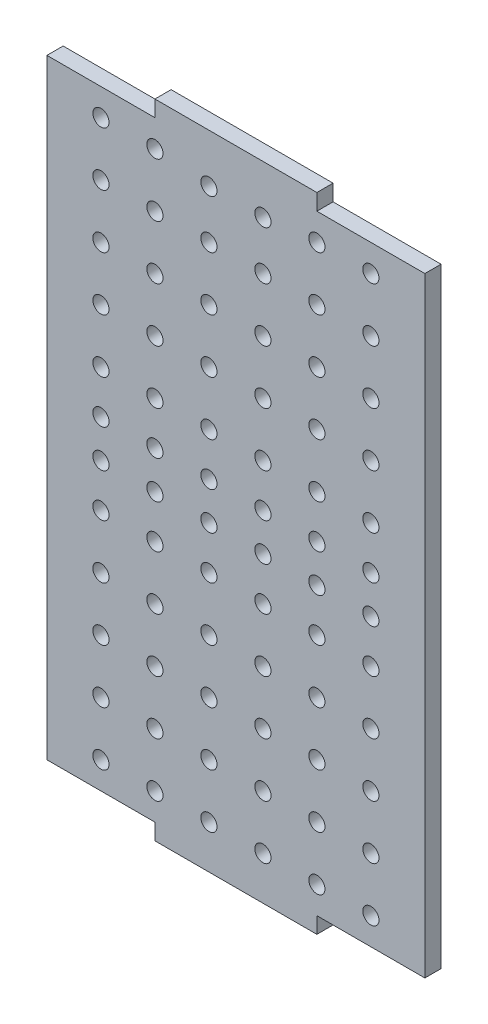
SolidWorks part; units mm, degrees
material "Maple"
ref_plane "Front Plane" through (0, 0, 0) normal (0, 0, 1) x (1, 0, 0)
ref_plane "Top Plane" through (0, 0, 0) normal (0, 1, 0) x (1, 0, 0)
ref_plane "Right Plane" through (0, 0, 0) normal (1, 0, 0) x (0, 0, -1)
sketch "Sketch1" plane through (0, 0, 0) normal (0, 0, 1) x (1, 0, 0)
  line L0 (-25, 56.5) -> (-25, 51.5) construction
  line L2 (-35, 56.5) -> (-35, -56.5)
  line L4 (35, 56.5) -> (35, -56.5)
  line L5 (-35, 56.5) -> (35, -56.5) construction
  line L6 (-35, -56.5) -> (35, 56.5) construction
  line L7 (-35, -56.5) -> (-15, -56.5)
  line L8 (-25, 51.5) -> (-25, 41.5) construction
  line L9 (-25, 41.5) -> (-25, 31.5) construction
  line L10 (-25, 31.5) -> (-25, 21.5) construction
  line L11 (-25, 21.5) -> (-25, 11.5) construction
  line L12 (-25, 11.5) -> (-25, 3.5) construction
  line L13 (-25, 3.5) -> (-25, -3.5) construction
  line L14 (-25, -3.5) -> (-25, -11.5) construction
  line L15 (-25, -11.5) -> (-25, -21.5) construction
  line L16 (-25, -21.5) -> (-25, -31.5) construction
  line L17 (-15, -41.5) -> (-15, -51.5) construction
  line L19 (-25, 41.5) -> (-15, 41.5) construction
  line L20 (25, 51.5) -> (25, 41.5) construction
  line L21 (-15, -56.5) -> (-15, -59.5)
  line L22 (35, -56.5) -> (15, -56.5)
  line L23 (-15, 41.5) -> (-5, 41.5) construction
  line L24 (-15, 51.5) -> (-15, 41.5) construction
  line L25 (-15, 41.5) -> (-15, 31.5) construction
  line L26 (-15, 31.5) -> (-15, 21.5) construction
  line L27 (-15, 21.5) -> (-15, 11.5) construction
  line L28 (-15, 11.5) -> (-15, 3.5) construction
  line L29 (-15, 3.5) -> (-15, -3.5) construction
  line L30 (-15, -3.5) -> (-15, -11.5) construction
  line L31 (-15, -11.5) -> (-15, -21.5) construction
  line L32 (-15, -21.5) -> (-15, -31.5) construction
  line L33 (-25, -41.5) -> (-25, -51.5) construction
  line L34 (25, 41.5) -> (25, 31.5) construction
  line L35 (25, 31.5) -> (25, 21.5) construction
  line L36 (25, 21.5) -> (25, 11.5) construction
  line L37 (-15, 51.5) -> (-15, 56.5) construction
  line L38 (-5, 50.5) -> (-5, 59.5) construction
  line L39 (5, 50.5) -> (5, 59.5) construction
  line L40 (-5, 51.5) -> (-5, 41.5) construction
  line L41 (-5, 41.5) -> (-5, 31.5) construction
  line L42 (-5, 31.5) -> (-5, 21.5) construction
  line L43 (-5, 21.5) -> (-5, 11.5) construction
  line L44 (-5, 11.5) -> (-5, 3.5) construction
  line L45 (-5, 3.5) -> (-5, -3.5) construction
  line L46 (-5, -3.5) -> (-5, -11.5) construction
  line L47 (-5, -11.5) -> (-5, -21.5) construction
  line L48 (-5, -21.5) -> (-5, -31.5) construction
  line L49 (-5, -41.5) -> (-5, -51.5) construction
  line L50 (25, 11.5) -> (25, 3.5) construction
  line L51 (25, 3.5) -> (25, -3.5) construction
  line L52 (25, -3.5) -> (25, -11.5) construction
  line L53 (15, 56.5) -> (15, 51.5) construction
  line L54 (-15, -59.5) -> (15, -59.5)
  line L55 (15, -59.5) -> (15, -56.5)
  line L56 (5, 51.5) -> (5, 41.5) construction
  line L57 (5, 41.5) -> (5, 31.5) construction
  line L58 (5, 31.5) -> (5, 21.5) construction
  line L59 (5, 21.5) -> (5, 11.5) construction
  line L60 (5, 11.5) -> (5, 3.5) construction
  line L61 (5, 3.5) -> (5, -3.5) construction
  line L62 (5, -3.5) -> (5, -11.5) construction
  line L63 (5, -11.5) -> (5, -21.5) construction
  line L64 (5, -21.5) -> (5, -31.5) construction
  line L65 (5, -41.5) -> (5, -51.5) construction
  line L66 (25, -11.5) -> (25, -21.5) construction
  line L67 (25, -21.5) -> (25, -31.5) construction
  line L68 (15, -41.5) -> (15, -51.5) construction
  line L69 (-5, 41.5) -> (5, 41.5) construction
  line L70 (5, 41.5) -> (15, 41.5) construction
  line L71 (15, 41.5) -> (25, 41.5) construction
  line L72 (15, 51.5) -> (15, 41.5) construction
  line L73 (15, 41.5) -> (15, 31.5) construction
  line L74 (15, 31.5) -> (15, 21.5) construction
  line L75 (15, 21.5) -> (15, 11.5) construction
  line L76 (15, 11.5) -> (15, 3.5) construction
  line L77 (15, 3.5) -> (15, -3.5) construction
  line L78 (15, -3.5) -> (15, -11.5) construction
  line L79 (15, -11.5) -> (15, -21.5) construction
  line L80 (15, -21.5) -> (15, -31.5) construction
  line L81 (25, -41.5) -> (25, -51.5) construction
  line L82 (25, 51.5) -> (25, 56.5) construction
  line L83 (-25, 56.5) -> (-15, 56.5)
  line L85 (25, 56.5) -> (35, 56.5)
  line L90 (-15, 56.5) -> (-15, 59.5)
  line L95 (-25, 56.5) -> (-35, 56.5)
  line L98 (25, 56.5) -> (15, 56.5)
  line L99 (15, 56.5) -> (15, 59.5)
  line L100 (15, 59.5) -> (5, 59.5)
  line L103 (-25, -31.5) -> (-25, -41.5) construction
  line L104 (-15, -31.5) -> (-15, -41.5) construction
  line L105 (-5, -31.5) -> (-5, -41.5) construction
  line L106 (5, -31.5) -> (5, -41.5) construction
  line L107 (25, -31.5) -> (25, -41.5) construction
  line L108 (15, -31.5) -> (15, -41.5) construction
  line L112 (-15, 59.5) -> (-5, 59.5)
  line L114 (-5, 59.5) -> (5, 59.5)
  circle A4 centre (-25, 51.5) radius 1.5
  circle A7 centre (-25, 41.5) radius 1.5
  circle A8 centre (-25, 31.5) radius 1.5
  circle A9 centre (-25, 21.5) radius 1.5
  circle A10 centre (-25, 11.5) radius 1.5
  circle A11 centre (-25, 3.5) radius 1.5
  circle A12 centre (-25, -3.5) radius 1.5
  circle A13 centre (-25, -11.5) radius 1.5
  circle A14 centre (-25, -21.5) radius 1.5
  circle A15 centre (-25, -31.5) radius 1.5
  circle A16 centre (-25, -51.5) radius 1.5
  circle A20 centre (-15, 51.5) radius 1.5
  circle A21 centre (-15, 41.5) radius 1.5
  circle A22 centre (-15, 31.5) radius 1.5
  circle A23 centre (-15, 21.5) radius 1.5
  circle A24 centre (-15, 11.5) radius 1.5
  circle A25 centre (-15, 3.5) radius 1.5
  circle A26 centre (-15, -3.5) radius 1.5
  circle A27 centre (-15, -11.5) radius 1.5
  circle A28 centre (-15, -21.5) radius 1.5
  circle A29 centre (-15, -31.5) radius 1.5
  circle A30 centre (-15, -51.5) radius 1.5
  circle A31 centre (-5, 50.5) radius 1.5
  circle A32 centre (-5, 41.5) radius 1.5
  circle A33 centre (-5, 31.5) radius 1.5
  circle A34 centre (-5, 21.5) radius 1.5
  circle A35 centre (-5, 11.5) radius 1.5
  circle A36 centre (-5, 3.5) radius 1.5
  circle A37 centre (-5, -3.5) radius 1.5
  circle A38 centre (-5, -11.5) radius 1.5
  circle A39 centre (-5, -21.5) radius 1.5
  circle A40 centre (-5, -31.5) radius 1.5
  circle A41 centre (-5, -51.5) radius 1.5
  circle A42 centre (5, 50.5) radius 1.5
  circle A43 centre (5, 41.5) radius 1.5
  circle A44 centre (5, 31.5) radius 1.5
  circle A45 centre (5, 21.5) radius 1.5
  circle A46 centre (5, 11.5) radius 1.5
  circle A47 centre (5, 3.5) radius 1.5
  circle A48 centre (5, -3.5) radius 1.5
  circle A49 centre (5, -11.5) radius 1.5
  circle A50 centre (5, -21.5) radius 1.5
  circle A51 centre (5, -31.5) radius 1.5
  circle A52 centre (5, -51.5) radius 1.5
  circle A53 centre (15, 51.5) radius 1.5
  circle A54 centre (15, 41.5) radius 1.5
  circle A55 centre (15, 31.5) radius 1.5
  circle A56 centre (15, 21.5) radius 1.5
  circle A57 centre (15, 11.5) radius 1.5
  circle A58 centre (15, 3.5) radius 1.5
  circle A59 centre (15, -3.5) radius 1.5
  circle A60 centre (15, -11.5) radius 1.5
  circle A61 centre (15, -21.5) radius 1.5
  circle A62 centre (15, -31.5) radius 1.5
  circle A63 centre (15, -51.5) radius 1.5
  circle A86 centre (25, 51.5) radius 1.5
  circle A87 centre (25, 41.5) radius 1.5
  circle A88 centre (25, 31.5) radius 1.5
  circle A89 centre (25, 21.5) radius 1.5
  circle A90 centre (25, 11.5) radius 1.5
  circle A91 centre (25, 3.5) radius 1.5
  circle A92 centre (25, -3.5) radius 1.5
  circle A93 centre (25, -11.5) radius 1.5
  circle A94 centre (25, -21.5) radius 1.5
  circle A95 centre (25, -31.5) radius 1.5
  circle A96 centre (25, -51.5) radius 1.5
  circle A97 centre (-25, -41.5) radius 1.5
  circle A98 centre (-15, -41.5) radius 1.5
  circle A99 centre (-5, -41.5) radius 1.5
  circle A100 centre (5, -41.5) radius 1.5
  circle A101 centre (15, -41.5) radius 1.5
  circle A102 centre (25, -41.5) radius 1.5
  point P0 (0, 0)
  dimension "D3" = 113
  dimension "D4" = 3
  dimension "D11" = 9
  dimension "D12" = 5
  dimension "D2" = 10
  dimension "D5" = 7
  dimension "D6" = 56.5
  dimension "D7" = 70
  dimension "D8" = 5
  dimension "D9" = 3
  dimension "D10" = 3
  dimension "D13" = 30
  dimension "D14" = 10
  dimension "D15" = 8
extrude "Boss-Extrude1" add sketch "Sketch1" along normal blind 3
